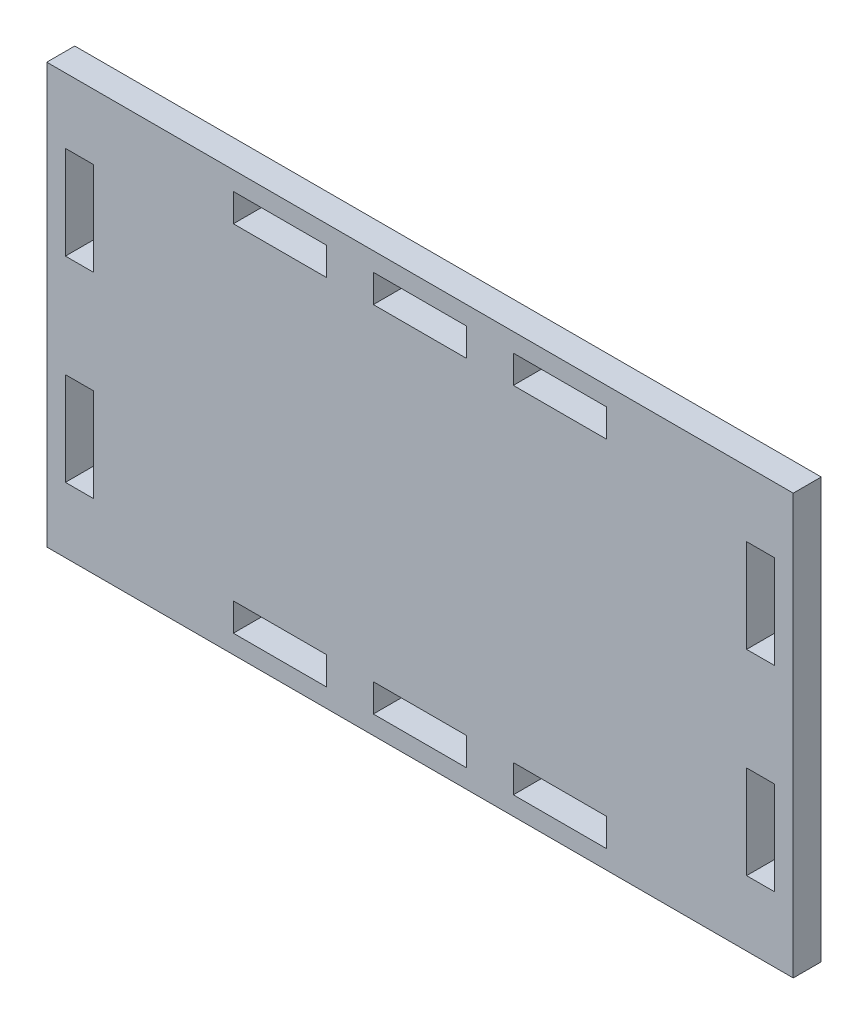
SolidWorks part; units mm, degrees
ref_plane "前视基准面" through (0, 0, 0) normal (0, 0, 1) x (1, 0, 0)
ref_plane "上视基准面" through (0, 0, 0) normal (0, 1, 0) x (1, 0, 0)
ref_plane "右视基准面" through (0, 0, 0) normal (1, 0, 0) x (0, 0, -1)
sketch "草图1" plane through (0, 0, 0) normal (0, 0, 1) x (1, 0, 0)
  line L0 (5, 20.5) -> (5, 17.5)
  line L1 (-40, 22.5) -> (40, 22.5)
  line L2 (-40, 22.5) -> (-40, -22.5)
  line L3 (-40, -22.5) -> (40, -22.5)
  line L4 (40, 22.5) -> (40, -22.5)
  line L5 (-40, 22.5) -> (40, -22.5) construction
  line L6 (-40, -22.5) -> (40, 22.5) construction
  line L7 (-10, 20.5) -> (-20, 20.5)
  line L8 (-10, 20.5) -> (-10, 17.5)
  line L9 (-10, 17.5) -> (-20, 17.5)
  line L10 (-20, 20.5) -> (-20, 17.5)
  line L11 (-38, 15.5) -> (-35, 15.5)
  line L12 (-38, 15.5) -> (-38, 5.5)
  line L13 (-38, 5.5) -> (-35, 5.5)
  line L14 (-35, 15.5) -> (-35, 5.5)
  line L15 (5, 20.5) -> (-5, 20.5)
  line L16 (-5, 20.5) -> (-5, 17.5)
  line L17 (5, 17.5) -> (-5, 17.5)
  line L18 (20, 20.5) -> (20, 17.5)
  line L19 (20, 20.5) -> (10, 20.5)
  line L20 (10, 20.5) -> (10, 17.5)
  line L21 (20, 17.5) -> (10, 17.5)
  line L22 (55, 0) -> (-55, 0) construction
  line L23 (20, -20.5) -> (10, -20.5)
  line L24 (10, -20.5) -> (10, -17.5)
  line L25 (20, -17.5) -> (10, -17.5)
  line L26 (20, -20.5) -> (20, -17.5)
  line L27 (5, -20.5) -> (-5, -20.5)
  line L28 (-5, -20.5) -> (-5, -17.5)
  line L29 (5, -17.5) -> (-5, -17.5)
  line L30 (5, -20.5) -> (5, -17.5)
  line L31 (-10, -17.5) -> (-20, -17.5)
  line L32 (-20, -20.5) -> (-20, -17.5)
  line L33 (-10, -20.5) -> (-20, -20.5)
  line L34 (-10, -20.5) -> (-10, -17.5)
  line L35 (-38, -5.5) -> (-35, -5.5)
  line L36 (-35, -15.5) -> (-35, -5.5)
  line L37 (-38, -15.5) -> (-35, -15.5)
  line L38 (-38, -15.5) -> (-38, -5.5)
  line L39 (0, -55) -> (0, 55) construction
  line L40 (38, -15.5) -> (38, -5.5)
  line L41 (38, -15.5) -> (35, -15.5)
  line L42 (35, -15.5) -> (35, -5.5)
  line L43 (38, -5.5) -> (35, -5.5)
  line L44 (38, 5.5) -> (35, 5.5)
  line L45 (35, 15.5) -> (35, 5.5)
  line L46 (38, 15.5) -> (35, 15.5)
  line L47 (38, 15.5) -> (38, 5.5)
  point P0 (0, 0)
  dimension "D1" = 80
  dimension "D2" = 45
  dimension "D3" = 10
  dimension "D4" = 3
  dimension "D5" = 10
  dimension "D6" = 3
  dimension "D7" = 2
  dimension "D8" = 2
  dimension "D9" = 20
  dimension "D10" = 7
  dimension "D11" = 3
extrude "凸台-拉伸1" add sketch "草图1" along normal blind 3
